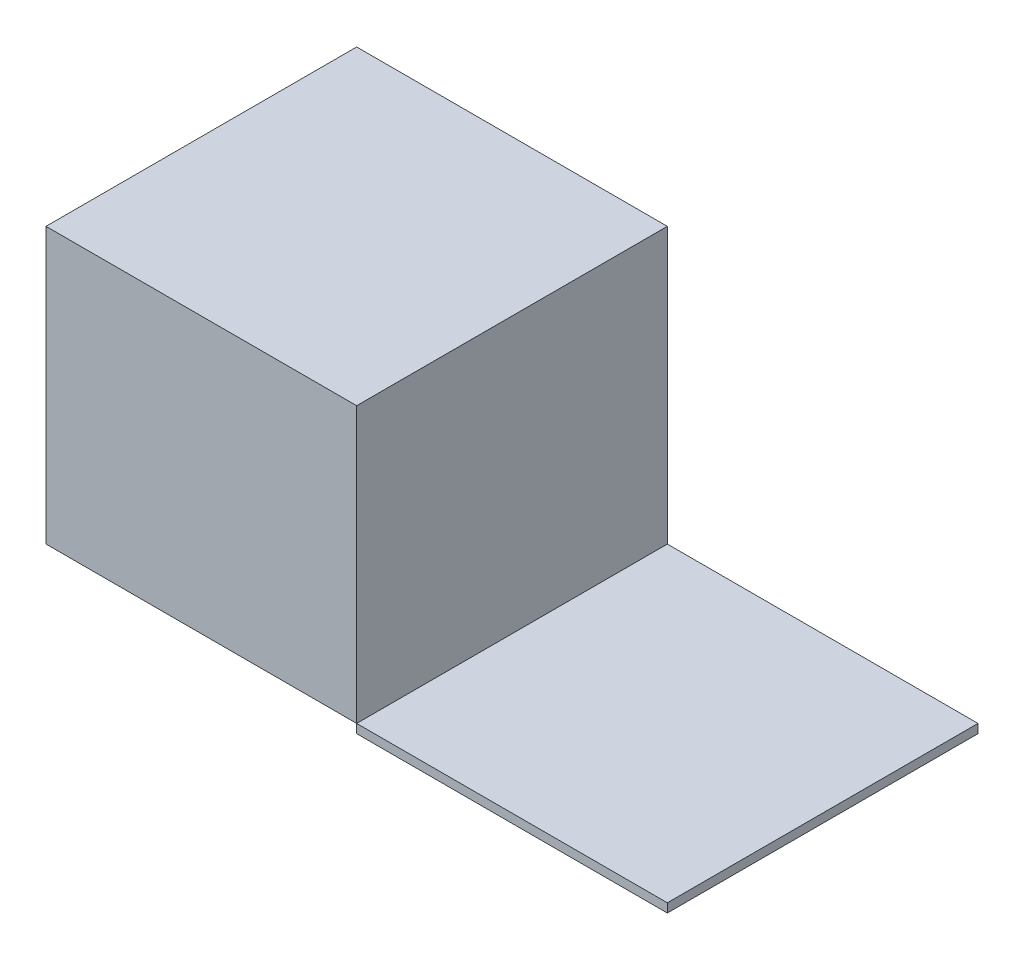
SolidWorks part; units mm, degrees
ref_plane "Front Plane" through (0, 0, 0) normal (0, 0, 1) x (1, 0, 0)
ref_plane "Top Plane" through (0, 0, 0) normal (0, 1, 0) x (1, 0, 0)
ref_plane "Right Plane" through (0, 0, 0) normal (1, 0, 0) x (0, 0, -1)
sketch "Sketch1" plane through (0, 0, 0) normal (0, 1, 0) x (1, 0, 0)
  line L0 (1, 1) -> (34, 1)
  line L1 (0, 0) -> (35, 0)
  line L2 (0, 0) -> (0, 35)
  line L3 (0, 35) -> (35, 35)
  line L4 (35, 0) -> (35, 35)
  line L5 (0, 0) -> (35, 35) construction
  line L6 (0, 35) -> (35, 0) construction
  line L7 (34, 1) -> (34, 34)
  line L8 (1, 34) -> (34, 34)
  line L9 (1, 1) -> (1, 34)
  point P4 (17.5, 17.5)
  dimension "D1" = 35
  dimension "D2" = 35
  dimension "D3" = 1
extrude "Boss-Extrude1" add sketch "Sketch1" along normal blind 30
sketch "Sketch2" plane through (0, 30, 0) normal (0, 1, 0) x (1, 0, 0)
  line L1 (0, 0) -> (35, 0)
  line L2 (0, 0) -> (0, 35)
  line L3 (0, 35) -> (35, 35)
  line L4 (35, 0) -> (35, 35)
  line L5 (0, 0) -> (35, 35) construction
  line L6 (0, 35) -> (35, 0) construction
  point P4 (17.5, 17.5)
extrude "Boss-Extrude2" add sketch "Sketch2" along normal blind 1
sketch "Sketch3" plane through (0, 0, 0) normal (0, -1, 0) x (1, 0, 0)
  line L0 (35, 0) -> (35, -35) construction
  line L1 (35, 0) -> (70, 0)
  line L2 (35, 0) -> (35, -35)
  line L3 (35, -35) -> (70, -35)
  line L4 (70, 0) -> (70, -35)
  line L5 (35, 0) -> (70, -35) construction
  line L6 (35, -35) -> (70, 0) construction
  point P4 (52.5, -17.5)
  dimension "D1" = 35
  dimension "D2" = 35
extrude "Boss-Extrude3" add sketch "Sketch3" along normal blind 1 separate body
